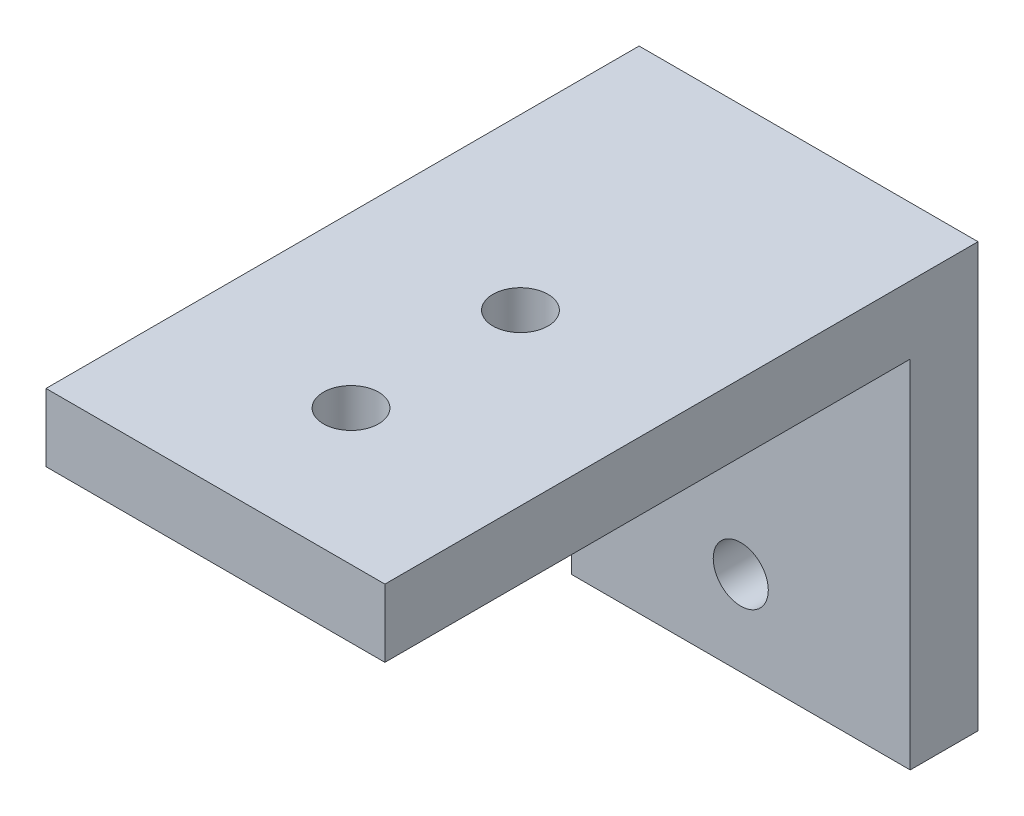
SolidWorks part; units mm, degrees
material "6061-T6 (SS)"
ref_plane "前视基准面" through (0, 0, 0) normal (0, 0, 1) x (1, 0, 0)
ref_plane "上视基准面" through (0, 0, 0) normal (0, 1, 0) x (1, 0, 0)
ref_plane "右视基准面" through (0, 0, 0) normal (1, 0, 0) x (0, 0, -1)
other "Configuration Table"
sketch "草图1" plane through (0, 0, 0) normal (0, 0, 1) x (1, 0, 0)
  line L0 (-20, -50) -> (20, -50)
  line L1 (20, -50) -> (20, 0)
  line L2 (20, 0) -> (-20, 0)
  line L3 (-20, 0) -> (-20, -50)
extrude "凸台-拉伸1" add sketch "草图1" along normal blind 8
sketch "草图2" plane through (0, 0, 0) normal (0, 0, 1) x (1, 0, 0)
  line L0 (-20, -8) -> (20, -8)
  line L1 (20, -8) -> (20, 0)
  line L2 (20, 0) -> (-20, 0)
  line L3 (-20, 0) -> (-20, -8)
extrude "凸台-拉伸2" add sketch "草图2" along normal blind 70
sketch "草图3" plane through (0, 0, 0) normal (0, 0, -1) x (-1, 0, 0)
  circle A0 centre (0, -20) radius 3.25
  circle A1 centre (0, -40) radius 3.25
extrude "切除-拉伸1" cut sketch "草图3" against normal blind 9
sketch "草图4" plane through (0, -8, 0) normal (0, -1, 0) x (1, 0, 0)
  circle A0 centre (0, 34) radius 3.25
  circle A1 centre (0, 54) radius 3.25
extrude "切除-拉伸2" cut sketch "草图4" against normal blind 8
